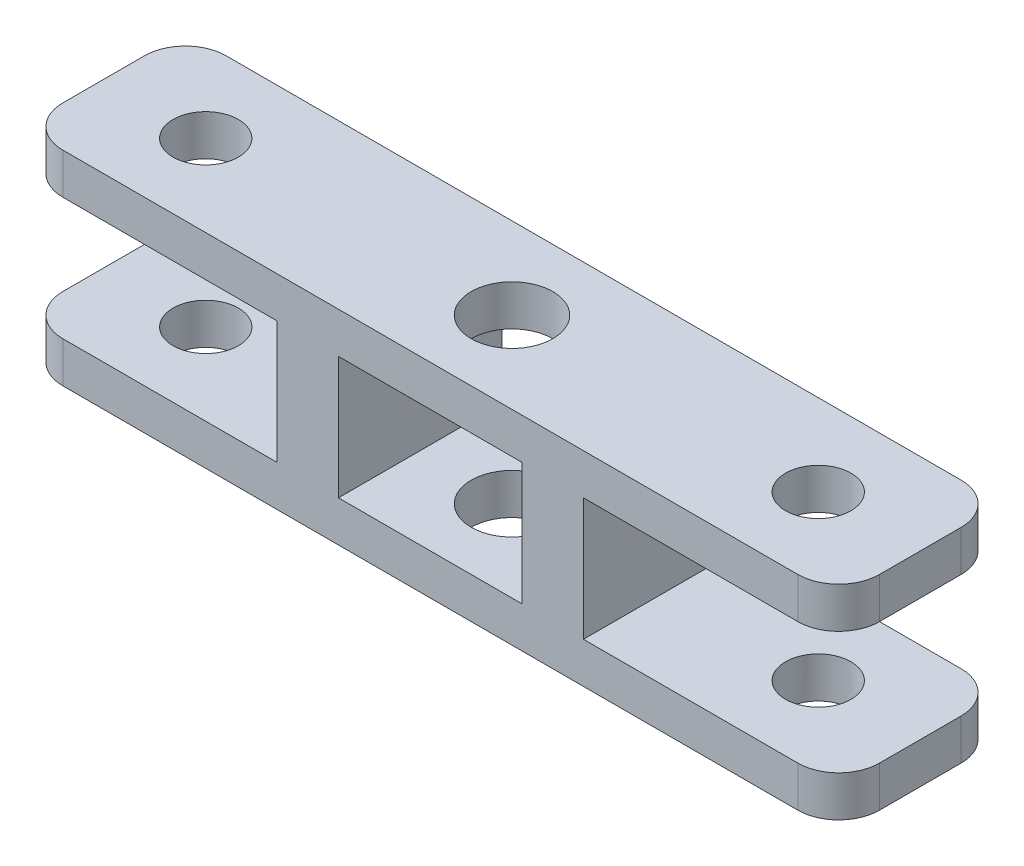
SolidWorks part; units mm, degrees
ref_plane "前视基准面" through (0, 0, 0) normal (0, 0, 1) x (1, 0, 0)
ref_plane "上视基准面" through (0, 0, 0) normal (0, 1, 0) x (1, 0, 0)
ref_plane "右视基准面" through (0, 0, 0) normal (1, 0, 0) x (0, 0, -1)
sketch "草图1" plane through (0, 0, 0) normal (0, 1, 0) x (1, 0, 0)
  line L1 (-20, -4) -> (20, -4)
  line L2 (-20, -4) -> (-20, 4)
  line L3 (-20, 4) -> (20, 4)
  line L4 (20, -4) -> (20, 4)
  line L5 (-20, -4) -> (20, 4) construction
  line L6 (-20, 4) -> (20, -4) construction
  point P0 (0, 0)
  dimension "D1" = 40
  dimension "D2" = 8
extrude "凸台-拉伸1" add sketch "草图1" along normal blind 2
sketch "草图2" plane through (0, 2, 0) normal (0, 1, 0) x (1, 0, 0)
  circle A0 centre (0, 0) radius 2
  dimension "D1" = 4
extrude "切除-拉伸1" cut sketch "草图2" against normal up to next
sketch "草图3" plane through (0, 2, 0) normal (0, 1, 0) x (1, 0, 0)
  line L0 (0, 5.4202) -> (0, -6.7281) construction
  line L1 (-9.4285, 0) -> (12.171, 0) construction
  circle A0 centre (15, 0) radius 1.6
  circle A1 centre (-15, 0) radius 1.6
  dimension "D1" = 15
  dimension "D2" = 3.2
extrude "切除-拉伸2" cut sketch "草图3" against normal up to next
sketch "草图4" plane through (0, 2, 0) normal (0, 1, 0) x (1, 0, 0)
  line L0 (0, 7.7713) -> (0, -7.9681) construction
  line L1 (-16.8871, 0) -> (20.5268, 0) construction
  line L2 (20, 4) -> (-20, 4) construction
  line L3 (-7.5, -4) -> (-4.5, -4)
  line L4 (-7.5, -4) -> (-7.5, 4)
  line L5 (-7.5, 4) -> (-4.5, 4)
  line L6 (-4.5, -4) -> (-4.5, 4)
  line L7 (-7.5, -4) -> (-4.5, 4) construction
  line L8 (-7.5, 4) -> (-4.5, -4) construction
  line L9 (7.5, 4) -> (4.5, -4) construction
  line L10 (7.5, -4) -> (4.5, 4) construction
  line L11 (4.5, -4) -> (4.5, 4)
  line L12 (7.5, 4) -> (4.5, 4)
  line L13 (7.5, -4) -> (7.5, 4)
  line L14 (7.5, -4) -> (4.5, -4)
  point P5 (-6, 0)
  point P16 (6, 0)
  dimension "D1" = 9
  dimension "D2" = 3
extrude "凸台-拉伸2" add sketch "草图4" along normal blind 6
sketch "草图5" plane through (0, 8, 0) normal (0, 1, 0) x (1, 0, 0)
  line L1 (-20, -4) -> (20, -4)
  line L2 (-20, -4) -> (-20, 4)
  line L3 (-20, 4) -> (20, 4)
  line L4 (20, -4) -> (20, 4)
  line L5 (-20, -4) -> (20, 4) construction
  line L6 (-20, 4) -> (20, -4) construction
  circle A0 centre (15, 0) radius 1.6 construction
  circle A1 centre (0, 0) radius 2 construction
  circle A2 centre (-15, 0) radius 1.6 construction
  circle A3 centre (15, 0) radius 1.6
  circle A4 centre (0, 0) radius 2
  circle A5 centre (-15, 0) radius 1.6
  point P0 (0, 0)
extrude "凸台-拉伸3" add sketch "草图5" along normal blind 2
fillet "圆角1" radius 2 8 edges at (20, 1, 4) (20, 9, 4) (20, 1, -4) (20, 9, -4) (-20, 1, -4) (-20, 9, -4) (-20, 1, 4) (-20, 9, 4)
